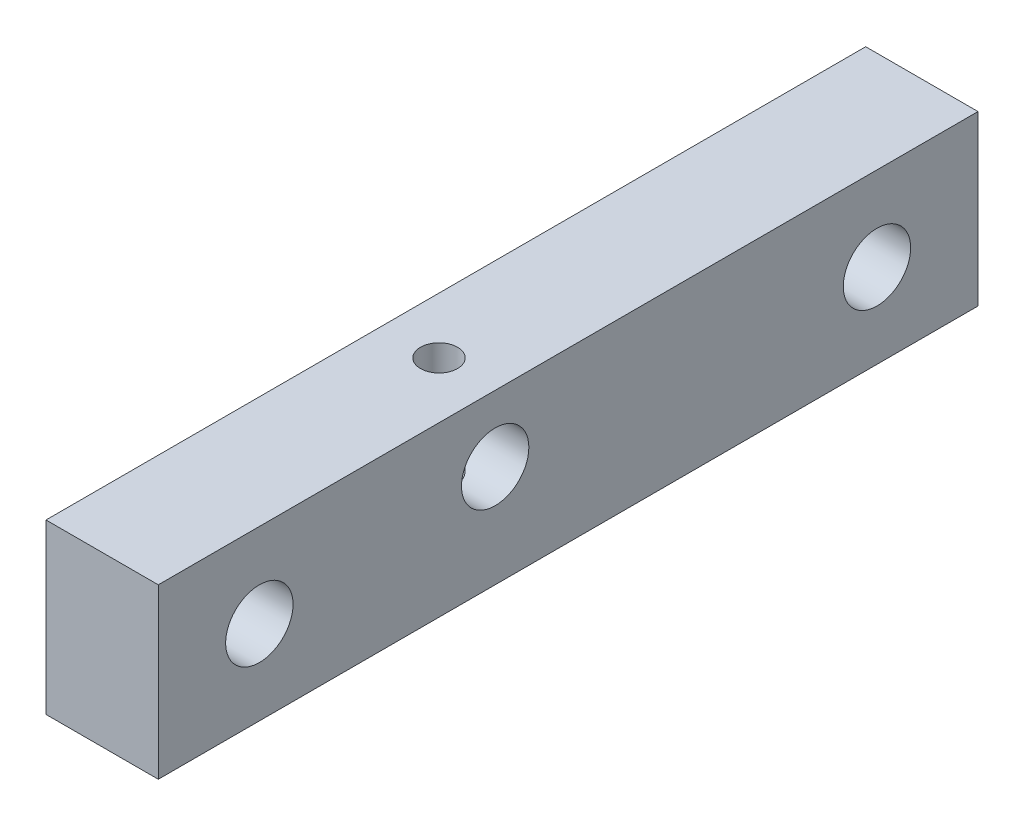
SolidWorks part; units mm, degrees
ref_plane "Front Plane" through (0, 0, 0) normal (0, 0, 1) x (1, 0, 0)
ref_plane "Top Plane" through (0, 0, 0) normal (0, 1, 0) x (1, 0, 0)
ref_plane "Right Plane" through (0, 0, 0) normal (1, 0, 0) x (0, 0, -1)
sketch "Sketch1" plane through (0, 0, 0) normal (0, 0, 1) x (1, 0, 0)
  line L1 (-5, -7.5) -> (5, -7.5)
  line L2 (-5, -7.5) -> (-5, 7.5)
  line L3 (-5, 7.5) -> (5, 7.5)
  line L4 (5, -7.5) -> (5, 7.5)
  line L5 (-5, -7.5) -> (5, 7.5) construction
  line L6 (-5, 7.5) -> (5, -7.5) construction
  point P0 (0, 0)
  dimension "D1" = 10
  dimension "D2" = 15
extrude "Boss-Extrude1" add sketch "Sketch1" against normal blind 73
sketch "Sketch2" plane through (5, 0, 0) normal (1, 0, 0) x (0, 0, -1)
  point P0 (9, 0)
  point P1 (64, 0)
hole_wizard "Ø6.0 (6) Diameter Hole1" positions "Sketch4" profile "Sketch3" hole size "Ø6.0" standard "ANSI Metric" end condition through all
sketch "Sketch4" plane through (5, 0, 0) normal (1, 0, 0) x (0, 0, -1)
  point P0 (9, 0)
  point P3 (64, 0)
sketch "Sketch3" plane through (5, 0, -9) normal (0, 1, 0) x (0, 0, -1)
  line L0 (0, 0) -> (0, 10)
  line L1 (0, 10) -> (3, 10)
  line L2 (3, 10) -> (3, 0)
  line L5 (3, 0) -> (0, 0)
  line L11 (0, -6.35) -> (0, 107.95) construction
  dimension "Thru Hole Dia." = 6
  dimension "Thru Hole Depth" = 10
sketch "Sketch5" plane through (5, 0, 0) normal (1, 0, 0) x (0, 0, -1)
  line L0 (73, 7.5) -> (0, 7.5) construction
  point P6 (30, 1.6)
  dimension "D1" = 5.9
hole_wizard "Ø6.0 (6) Diameter Hole2" positions "Sketch7" profile "Sketch8" hole size "Ø6.0" standard "ANSI Metric" end condition through all
sketch "Sketch7" plane through (5, 0, 0) normal (1, 0, 0) x (0, 0, -1)
  point P0 (30, 1.6)
sketch "Sketch8" plane through (5, 1.6, -30) normal (0, 1, 0) x (0, 0, -1)
  line L0 (0, 0) -> (0, 10)
  line L1 (0, 10) -> (3, 10)
  line L2 (3, 10) -> (3, 0)
  line L5 (3, 0) -> (0, 0)
  line L11 (0, -6.35) -> (0, 107.95) construction
  dimension "Thru Hole Dia." = 6
  dimension "Thru Hole Depth" = 10
sketch "Sketch9" plane through (0, 7.5, 0) normal (0, 1, 0) x (1, 0, 0)
  line L0 (-5, 33) -> (-5, 27) construction
  line L1 (5, 0) -> (-5, 0) construction
  point P0 (0, 30)
  dimension "D1" = 5
  dimension "D2" = 30
hole_wizard "M4x0.7 Tapped Hole1" positions "Sketch11" profile "Sketch10" tap size "M4x0.7" standard "ANSI Metric" end condition through all
sketch "Sketch11" plane through (0, 7.5, 0) normal (0, 1, 0) x (1, 0, 0)
  point P0 (0, 30)
cosmetic thread "Hole Thread1" parameters "D2"=4
sketch "Sketch10" plane through (0, 7.5, -30) normal (1, 0, 0) x (0, 0, 1)
  line L0 (0, 0) -> (0, 15)
  line L1 (0, 15) -> (1.65, 15)
  line L2 (1.65, 15) -> (1.65, 0)
  line L5 (1.65, 0) -> (0, 0)
  line L11 (0, -6.35) -> (0, 107.95) construction
  dimension "Thru Tap Drill Dia." = 3.3
  dimension "Thru Tap Drill Depth" = 15
